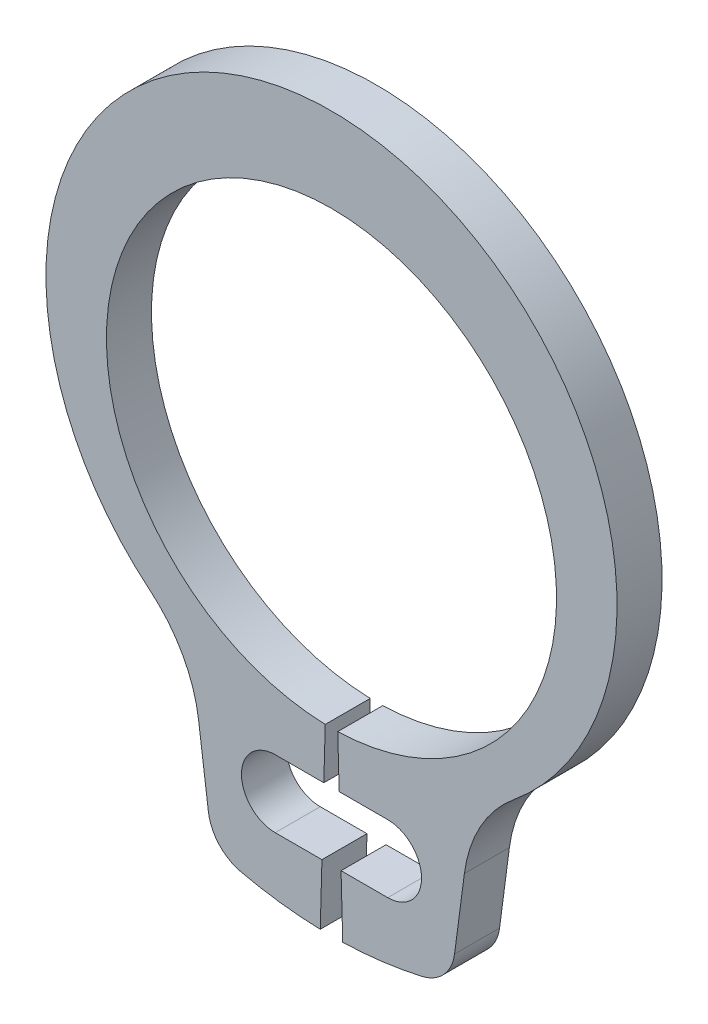
SolidWorks part; units mm, degrees
ref_plane "Plane1" through (0, 0, 0) normal (0, 0, 1) x (1, 0, 0)
ref_plane "Plane2" through (0, 0, 0) normal (0, 1, 0) x (1, 0, 0)
ref_plane "Plane3" through (0, 0, 0) normal (1, 0, 0) x (0, 0, -1)
sketch "Clipboard" plane through (0, 0, 0) normal (0, 0, 1) x (1, 0, 0)
  line L0 (0, 0) -> (1.5, 0)
  line L1 (0, 0) -> (0, 0.75)
  line L2 (0, 0) -> (0, -3.2)
  circle A0 centre (0, 0) radius 0.6
  circle A1 centre (0, 0) radius 4
  dimension "HoleDia" = 1.2
  dimension "ShaftDia" = 8
  dimension "LargeSection" = 1.5
  dimension "SmallSection" = 0.75
  dimension "LugSection" = 3.2
sketch "BodySke" plane through (0, 0, 0) normal (0, 0, 1) x (1, 0, 0)
  line L0 (-1.5431, 0) -> (1.5431, 0) construction
  line L1 (0, 0) -> (0, 5.5) construction
  line L2 (0.1111, -3.9985) -> (0.2, -7.1972)
  line L3 (-0.1111, -3.9985) -> (-0.2, -7.1972)
  line L4 (0, 0) -> (4.7885, -5.3768) construction
  line L5 (0, 0) -> (-4.7885, -5.3768) construction
  line L7 (2.362, -5.0574) -> (2.1873, -6.3842)
  line L8 (-2.362, -5.0574) -> (-2.1873, -6.3842)
  circle A0 centre (0, 0) radius 4 construction
  arc A1 (0.1111, -3.9985) -> (-0.1111, -3.9985) centre (0, 0) ccw
  arc A2 (3.1591, -3.5472) -> (-3.1591, -3.5472) centre (0, 0.4249) ccw construction
  arc A3 (0.2, -7.1972) -> (1.6116, -7.0173) centre (0, 0) ccw
  arc A4 (3.2306, -3.4893) -> (2.362, -5.0574) centre (4.7885, -5.3768) ccw
  arc A5 (-2.362, -5.0574) -> (-3.2306, -3.4893) centre (-4.7885, -5.3768) ccw
  arc A6 (-1.6116, -7.0173) -> (-0.2, -7.1972) centre (0, 0) ccw
  arc A7 (3.2306, -3.4893) -> (-3.2306, -3.4893) centre (0, 0.4249) ccw
  arc A8 (-2.3592, -5.0788) -> (2.3592, -5.0788) centre (0, 0) ccw construction
  circle A9 centre (1, -5.51) radius 0.6
  circle A10 centre (-1, -5.51) radius 0.6
  arc A11 (2.1873, -6.3842) -> (1.6116, -7.0173) centre (1.4437, -6.2863) cw
  arc A12 (-2.1873, -6.3842) -> (-1.6116, -7.0173) centre (-1.4437, -6.2863) ccw
  point P28 (2.122, -6.8802)
  point P31 (-2.122, -6.8802)
  dimension "HoleDia" = 1.2
  dimension "GrooveDia" = 8
  dimension "LugRad" = 7.2
  dimension "HoleOffsetRad" = 5.6
  dimension "D3" = 0.75
  dimension "LargeRad" = 5.5
  dimension "SmallRad" = 4.75
  dimension "SmallAngle" = 83.375
  dimension "D2" = 15
  dimension "HoleSpacing" = 2
  dimension "Gap" = 0.4
extrude "Body" add sketch "BodySke" against normal blind 0.8
sketch "NotSke" plane through (0, 0, 0) normal (0, 0, 1) x (1, 0, 0)
  line L0 (1, -4.91) -> (1, -6.11)
  line L1 (1, -6.11) -> (-1, -6.11)
  line L2 (-1, -6.11) -> (-1, -4.91)
  line L3 (-1, -4.91) -> (1, -4.91)
  circle A0 centre (1, -5.51) radius 0.6 construction
  circle A1 centre (-1, -5.51) radius 0.6 construction
extrude "Notch" cut sketch "NotSke" against normal through all
sketch "UnlSke" plane through (0, 0, 0) normal (0, 0, 1) x (1, 0, 0)
  line L0 (-2.0373, -6.9057) -> (-1.1319, -3.8365)
  line L1 (2.0373, -6.9057) -> (1.1319, -3.8365)
  arc A0 (1.1319, -3.8365) -> (-1.1319, -3.8365) centre (0, 0) ccw
  arc A1 (2.0373, -6.9057) -> (-2.0373, -6.9057) centre (0, 0) ccw
  arc A2 (0.2, -7.1972) -> (1.6116, -7.0173) centre (0, 0) ccw construction
  arc A3 (0.1111, -3.9985) -> (-0.1111, -3.9985) centre (0, 0) ccw construction
  circle A4 centre (-1, -5.51) radius 0.6 construction
  circle A5 centre (1, -5.51) radius 0.6 construction
extrude "Unlug" [suppressed] add sketch "UnlSke" against normal through all
equation "' \"ShaftDia@Clipboard\" = 3"
equation "' \"Thickness@Body\" = 0.4"
equation "' \"GrooveDia@BodySke\" = 2.8"
equation "' \"LugSection@Clipboard\" = 1.9"
equation "' \"LargeSection@Clipboard\" = 0.8"
equation "' \"HoleDia@Clipboard\" = 1.0"
equation "' \"ShaftDia@Clipboard\" = 10"
equation "' \"Thickness@Body\" = 1.0"
equation "' \"GrooveDia@BodySke\" = 9.6"
equation "' \"LugSection@Clipboard\" = 3.3"
equation "' \"LargeSection@Clipboard\" = 1.8"
equation "' \"HoleDia@Clipboard\" = 1.5"
equation "\"SmallSection@Clipboard\" = \"LargeSection@Clipboard\" * 0.5"
equation "\"Gap@BodySke\" =  \"Thickness@Body\" / 2"
equation "\"LargeRad@BodySke\" =  \"GrooveDia@BodySke\" / 2 +  \"LargeSection@Clipboard\""
equation "\"SmallRad@BodySke\" =  \"GrooveDia@BodySke\" / 2 +  \"SmallSection@Clipboard\""
equation "\"LugRad@BodySke\" = \"GrooveDia@BodySke\" / 2 + \"LugSection@Clipboard\""
equation "\"HoleOffsetRad@BodySke\" = (  \"ShaftDia@Clipboard\" / 2 + \"LugRad@BodySke\" ) / 2"
equation "\"HoleSpacing@BodySke\" = \"Gap@BodySke\"  * 2 +  \"HoleDia@Clipboard\""
equation "\"HoleDia@BodySke\" =  \"HoleDia@Clipboard\""
equation "\"SmallAngle@BodySke\" = atn(\"HoleSpacing@BodySke\" / 2 / sqr(\"HoleOffsetRad@BodySke\"  * \"HoleOffsetRad@BodySke\" - (\"HoleSpacing@BodySke\" / 2) * (\"HoleSpacing@BodySke\" / 2) ))  * 7 *  (\"LargeRad@BodySke\" / \"SmallRad@BodySke\")* ( 180 / 3.141593)"
